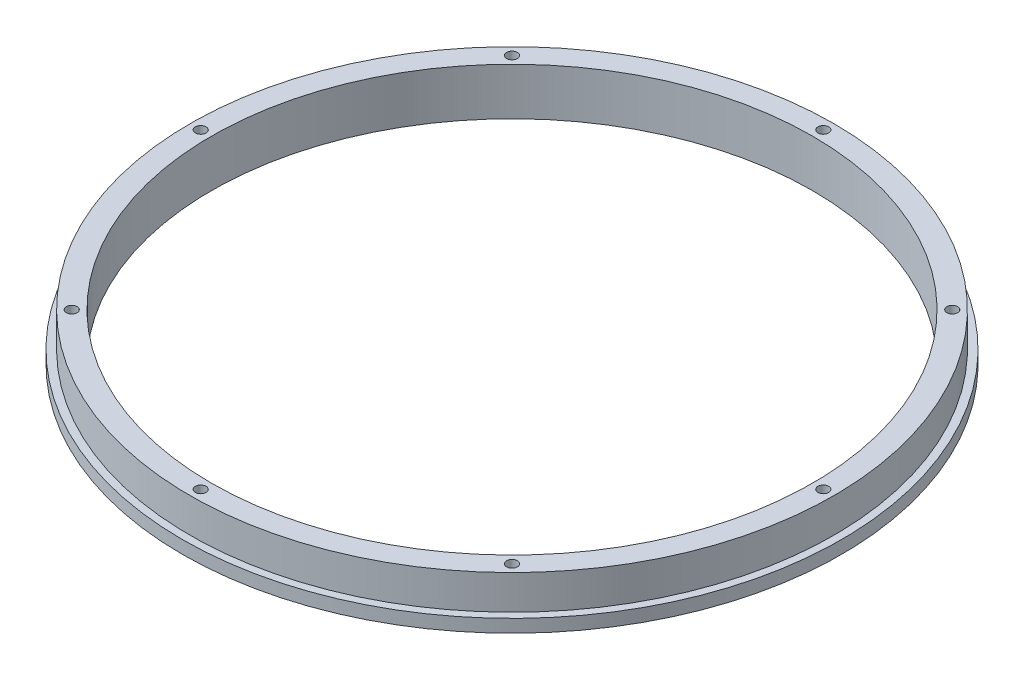
SolidWorks part; units mm, degrees
material "6061-T6 (SS)"
ref_plane "前视基准面" through (0, 0, 0) normal (0, 0, 1) x (1, 0, 0)
ref_plane "上视基准面" through (0, 0, 0) normal (0, 1, 0) x (1, 0, 0)
ref_plane "右视基准面" through (0, 0, 0) normal (1, 0, 0) x (0, 0, -1)
sketch "草图1" plane through (0, 0, 0) normal (0, 0, 1) x (1, 0, 0)
  line L0 (0, 51.6947) -> (0, -47.5565) construction
  line L1 (-69.0672, 0) -> (91.9671, 0) construction
  line L2 (70, 0) -> (76.75, 0)
  line L3 (76.75, 0) -> (76.75, 3)
  line L4 (76.75, 3) -> (75, 3)
  line L5 (75, 3) -> (75, 11)
  line L6 (75, 11) -> (70, 11)
  line L7 (70, 11) -> (70, 0)
  dimension "D1" = 3
  dimension "D2" = 153.5
  dimension "D3" = 8
  dimension "D4" = 150
  dimension "D5" = 5
revolve "旋转1" add sketch "草图1" angle 360 about L0
sketch "草图2" plane through (0, 11, 0) normal (0, 1, 0) x (1, 0, 0)
  line L0 (0, 89.275) -> (0, 0) construction
  circle A0 centre (0, 0) radius 72.5 construction
  point P4 (0, 72.5)
  point P5 (51.2652, 51.2652)
  point P8 (72.5, 0)
  point P9 (51.2652, -51.2652)
  point P10 (0, -72.5)
  point P11 (-51.2652, -51.2652)
  point P12 (-72.5, 0)
  point P13 (-51.2652, 51.2652)
  point P14 (0, 0)
  dimension "D1" = 145
  dimension "D2" = 8
hole_wizard "M3 螺纹孔1" positions "草图3" profile "草图5" tap size "M3" standard "GB" end condition through all
sketch "草图3" plane through (0, 11, 0) normal (0, 1, 0) x (1, 0, 0)
  point P0 (-51.2652, 51.2652)
  point P3 (0, 72.5)
  point P6 (51.2652, 51.2652)
  point P9 (72.5, 0)
  point P12 (51.2652, -51.2652)
  point P15 (0, -72.5)
  point P18 (-51.2652, -51.2652)
  point P21 (-72.5, 0)
sketch "草图5" plane through (-51.2652, 11, -51.2652) normal (1, 0, 0) x (0, 0, 1)
  line L0 (0, 0) -> (0, 11)
  line L1 (0, 11) -> (1.25, 11)
  line L2 (1.25, 11) -> (1.25, 0)
  line L5 (1.25, 0) -> (0, 0)
  line L11 (0, -6.35) -> (0, 107.95) construction
  dimension "通孔螺纹孔钻头直径" = 2.5
  dimension "通孔螺纹孔钻头深度" = 11
cosmetic thread "孔螺蚊线1" parameters "D2"=3
cosmetic thread "孔螺蚊线2" parameters "D2"=3
cosmetic thread "孔螺蚊线3" parameters "D2"=3
cosmetic thread "孔螺蚊线4" parameters "D2"=3
cosmetic thread "孔螺蚊线5" parameters "D2"=3
cosmetic thread "孔螺蚊线6" parameters "D2"=3
cosmetic thread "孔螺蚊线7" parameters "D2"=3
cosmetic thread "孔螺蚊线8" parameters "D2"=3
move or copy body "实体-移动/复制1" bodies to move or copy 107
